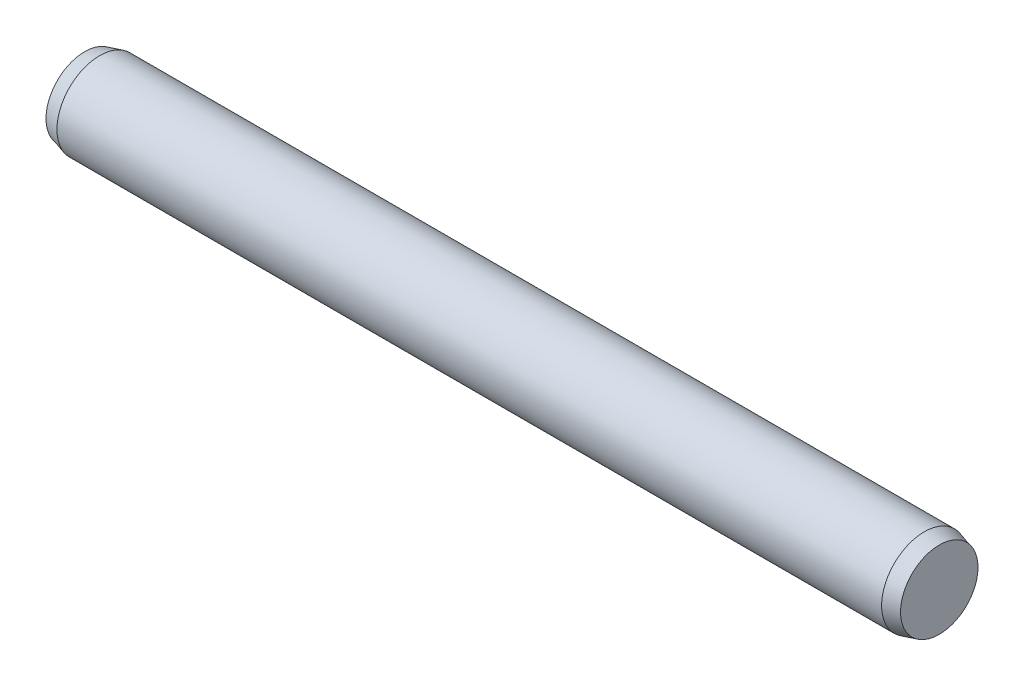
SolidWorks part; units mm, degrees
ref_plane "Front Plane" through (0, 0, 0) normal (0, 0, 1) x (1, 0, 0)
ref_plane "Top Plane" through (0, 0, 0) normal (0, 1, 0) x (1, 0, 0)
ref_plane "Right Plane" through (0, 0, 0) normal (1, 0, 0) x (0, 0, -1)
sketch "Sketch1" plane through (0, 0, 0) normal (0, 0, 1) x (1, 0, 0)
  line L0 (-9.65, 0) -> (9.65, 0) construction
  line L1 (9.65, 1) -> (9.65, -1) construction
  line L2 (-9.65, 1) -> (-9.65, -1) construction
  line L3 (10, 1) -> (10, -1) construction
  line L4 (-10, 1) -> (-10, -1) construction
  line L5 (-9.65, 0) -> (-10, 0) construction
  line L6 (9.65, 0) -> (10, 0) construction
  dimension "D1" = 0.35
  dimension "Dia" = 2
  dimension "Length" = 20
  dimension "C" = 0.35
sketch "Sketch2" plane through (0, 0, 0) normal (1, 0, 0) x (0, 0, -1)
  circle A0 centre (0, 0) radius 1
extrude "Extrude1" add sketch "Sketch2" against normal up to vertex (9.65 mm away) and the other way up to vertex (9.65 mm away) up to point (-9.65, 1, 0) other way up to point (9.65, 1, 0)
sketch "Sketch3" plane through (9.65, 0, 0) normal (1, 0, 0) x (0, 0, -1)
  circle A1 centre (0, 0) radius 1
  circle A2 centre (0, 0) radius 1
  dimension "D1" = 0
extrude "Extrude2" add sketch "Sketch3" along normal up to vertex (0.35 mm away) draft 15 up to point (10, 0, 0)
sketch "Sketch4" plane through (-9.65, 0, 0) normal (-1, 0, 0) x (0, 0, 1)
  circle A1 centre (0, 0) radius 1
  circle A2 centre (0, 0) radius 1
  dimension "D1" = 0
extrude "Extrude3" add sketch "Sketch4" along normal up to vertex (0.35 mm away) draft 15 up to point (-10, 0, 0)
equation "\"D1@Sketch1\" = \"C@Sketch1\""
